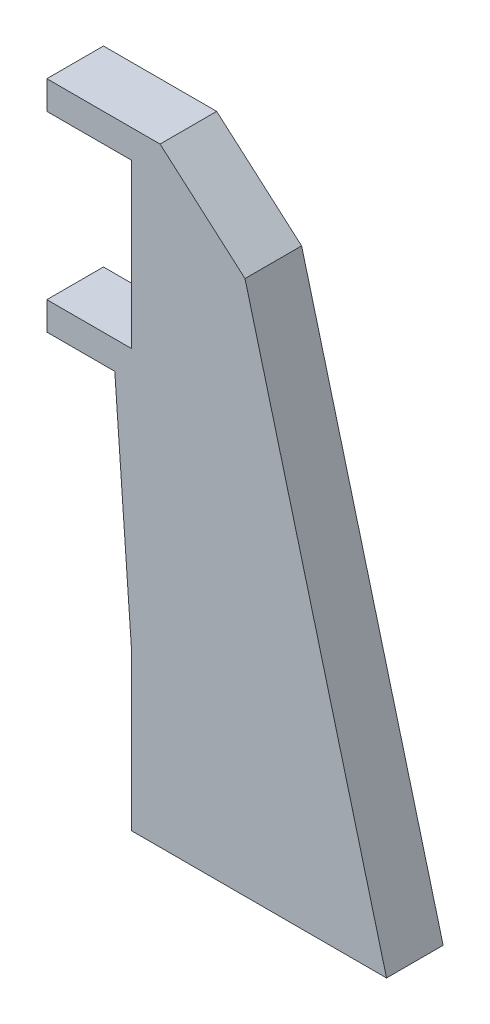
SolidWorks part; units mm, degrees
ref_plane "Front Plane" through (0, 0, 0) normal (0, 0, 1) x (1, 0, 0)
ref_plane "Top Plane" through (0, 0, 0) normal (0, 1, 0) x (1, 0, 0)
ref_plane "Right Plane" through (0, 0, 0) normal (1, 0, 0) x (0, 0, -1)
sketch "Sketch1" plane through (0, 0, 0) normal (0, 0, 1) x (1, 0, 0)
  line L0 (0, 0) -> (0, 12.7)
  line L1 (0, 12.7) -> (50.8, 12.7)
  line L2 (50.8, 12.7) -> (88.9, -20.5102)
  line L3 (0, 0) -> (38.0187, 0)
  line L4 (38.0187, 0) -> (38.0187, -73.1523)
  line L5 (38.0187, -73.1523) -> (0, -73.1523)
  line L6 (0, -73.1523) -> (0, -85.7639)
  line L7 (0, -85.7639) -> (30.48, -85.7639)
  line L10 (38.0187, -260.5159) -> (152.4, -260.5159)
  line L11 (152.4, -260.5159) -> (88.9, -20.5102)
  line L15 (30.48, -85.7639) -> (38.0187, -190.6965)
  line L16 (38.0187, -190.6965) -> (38.0187, -260.5159)
  dimension "D1" = 50.8
  dimension "D2" = 12.7
  dimension "D3" = 38.0187
  dimension "D4" = 73.1523
  dimension "D5" = 152.4
  dimension "D6" = 38.1
  dimension "D7" = 30.48
  dimension "D9" = 12.6117
  dimension "D10" = 174.752
extrude "Boss-Extrude1" add sketch "Sketch1" along normal blind 25.4
